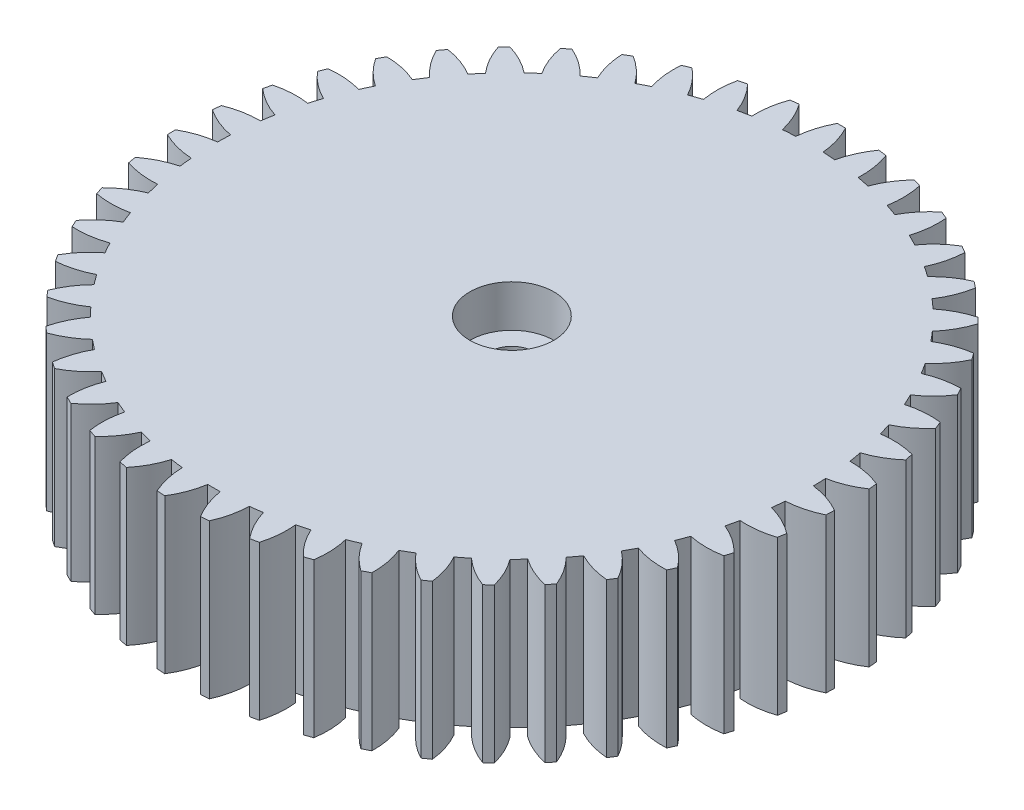
SolidWorks part; units mm, degrees
ref_plane "Front Plane" through (0, 0, 0) normal (0, 0, 1) x (1, 0, 0)
ref_plane "Top Plane" through (0, 0, 0) normal (0, 1, 0) x (1, 0, 0)
ref_plane "Right Plane" through (0, 0, 0) normal (1, 0, 0) x (0, 0, -1)
sketch "Sketch1" plane through (0, 0, 0) normal (0, 1, 0) x (1, 0, 0)
  circle A0 centre (0, 0) radius 21.25
  dimension "D1" = 42.5
extrude "Boss-Extrude1" add sketch "Sketch1" along normal blind 10.4
sketch "Sketch8" plane through (0, 0, 0) normal (0, -1, 0) x (-1, 0, 0)
  circle A0 centre (0, 0) radius 2.825
  dimension "D1" = 5.65
extrude "Cut-Extrude3" cut sketch "Sketch8" against normal blind 3.7
sketch "Sketch9" plane through (0, 10.4, 0) normal (0, 1, 0) x (1, 0, 0)
  arc A0 (-0.2927, 23.5105) -> (-0.9725, 21.2277) centre (5.0034, 20.6906) ccw
  arc A1 (0.9725, 21.2277) -> (0.2927, 23.5105) centre (-5.0034, 20.6906) ccw
  arc A2 (0.2927, 23.5105) -> (-0.2927, 23.5105) centre (0, 0) ccw
  arc A3 (-0.9725, 21.2277) -> (0.9725, 21.2277) centre (0, 0) cw
  dimension "D1" = 0.9725
  dimension "D2" = 0.9725
  dimension "D3" = 0.2927
  dimension "D4" = 0.2927
  dimension "D5" = 2.2828
  dimension "D6" = 21.2277
extrude "Boss-Extrude3" add sketch "Sketch9" against normal blind 11
pattern_circular "CirPattern1" count 47 over 360 about axis through (0, 0, 0) along (0, 1, 0) of "Boss-Extrude3"
sketch "Sketch10" plane through (0, 10.4, 0) normal (0, 1, 0) x (1, 0, 0)
  circle A0 centre (0, 0) radius 1.6
  dimension "D1" = 3.2
extrude "Cut-Extrude4" cut sketch "Sketch10" against normal blind 10
sketch "Sketch11" plane through (0, 10.4, 0) normal (0, 1, 0) x (1, 0, 0)
  circle A0 centre (0, 0) radius 3
  dimension "D1" = 6
extrude "Cut-Extrude5" cut sketch "Sketch11" against normal blind 3
